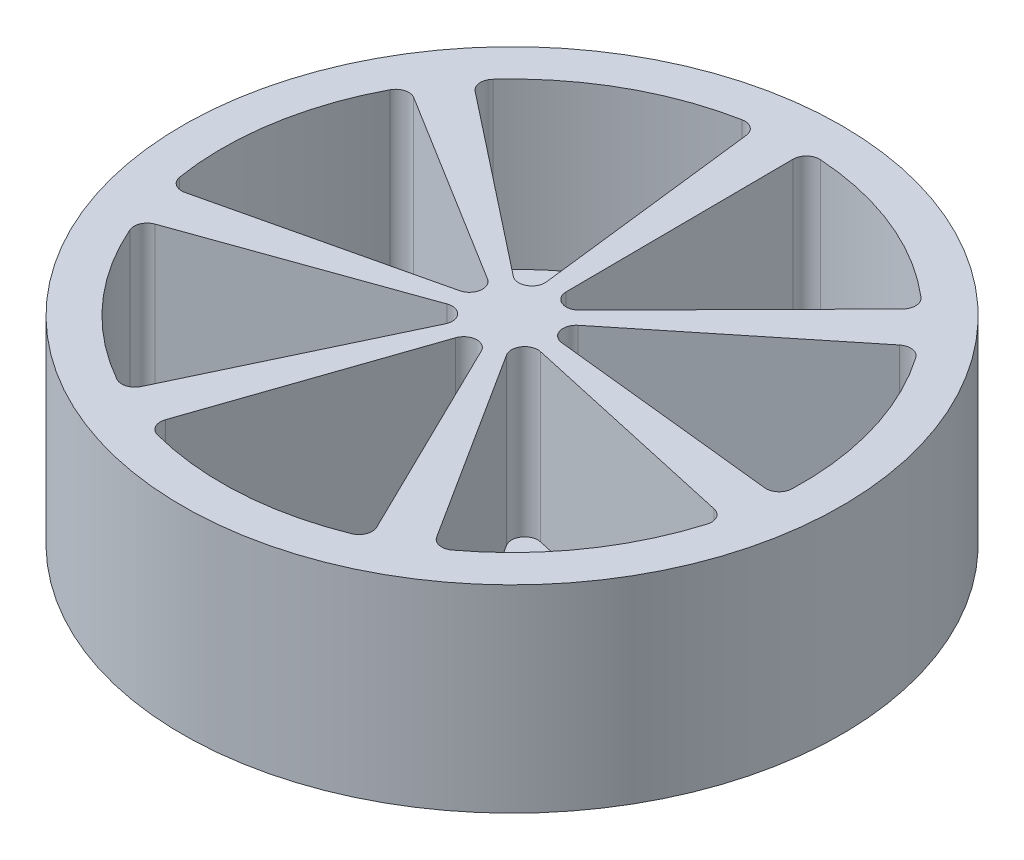
SolidWorks part; units mm, degrees
material "ABS"
ref_plane "Front Plane" through (0, 0, 0) normal (0, 0, 1) x (1, 0, 0)
ref_plane "Top Plane" through (0, 0, 0) normal (0, 1, 0) x (1, 0, 0)
ref_plane "Right Plane" through (0, 0, 0) normal (1, 0, 0) x (0, 0, -1)
sketch "Sketch1" plane through (0, 0, 0) normal (0, 1, 0) x (1, 0, 0)
  circle A0 centre (0, 0) radius 63.5
  dimension "D1" = 127
extrude "Boss-Extrude1" add sketch "Sketch1" along normal blind 38.1
sketch "Sketch2" plane through (0, 38.1, 0) normal (0, 1, 0) x (1, 0, 0)
  line L0 (-1.782, -9.1113) -> (-16.0573, -50.7387)
  line L1 (2.9021, -8.8187) -> (22.2474, -48.3457)
  line L2 (0.2069, -3.3118) -> (23.4176, -50.7365) construction
  line L3 (0, 0) -> (25.1229, -51.3319) construction
  line L4 (0, 0) -> (-18.5387, -54.0596) construction
  line L5 (0.2069, -3.3118) -> (-16.9208, -53.2566) construction
  line L6 (8.7042, -3.2294) -> (51.6692, -12.7493)
  line L9 (6.0125, -7.074) -> (29.6575, -44.1892)
  line L10 (7.9518, 4.7917) -> (42.183, 32.4476)
  line L11 (9.2794, 0.2902) -> (53.0397, -4.3643)
  line L12 (1.2116, 9.2045) -> (0.9321, 53.2107)
  line L13 (5.5587, 7.4359) -> (36.4818, 38.747)
  line L14 (-6.441, 6.6862) -> (-41.0207, 33.9051)
  line L15 (-2.3478, 8.9822) -> (-7.5476, 52.681)
  line L16 (-9.2434, -0.867) -> (-52.0841, -10.9317)
  line L17 (-8.4864, 3.7647) -> (-45.8935, 26.9451)
  line L18 (-5.0853, -7.7673) -> (-23.9271, -47.5368)
  line L19 (-8.2345, -4.2876) -> (-49.6807, -19.081)
  arc A0 (-18.5387, -54.0596) -> (25.1229, -51.3319) centre (0, 0) ccw construction
  circle A1 centre (0, 0) radius 63.5 construction
  arc A2 (-14.3049, -54.018) -> (20.9168, -51.8176) centre (0, 0) ccw
  arc A3 (-16.9208, -53.2566) -> (23.4176, -50.7365) centre (0, 0) ccw construction
  arc A4 (20.9168, -51.8176) -> (22.2474, -48.3457) centre (19.966, -49.4622) ccw
  arc A5 (-16.0573, -50.7387) -> (-14.3049, -54.018) centre (-13.6547, -51.5626) ccw
  arc A6 (-1.782, -9.1113) -> (2.9021, -8.8187) centre (0.6207, -9.9353) cw
  arc A7 (6.0125, -7.074) -> (8.7042, -3.2294) centre (8.1547, -5.7093) cw
  arc A8 (33.314, -44.8637) -> (53.554, -15.9543) centre (0, 0) ccw
  arc A9 (29.6575, -44.1892) -> (33.314, -44.8637) centre (31.7998, -42.8244) ccw
  arc A10 (53.554, -15.9543) -> (51.6692, -12.7493) centre (51.1198, -15.2291) ccw
  arc A11 (9.2794, 0.2902) -> (7.9518, 4.7917) centre (9.548, 2.8159) cw
  arc A12 (55.8468, -1.9261) -> (45.864, 31.9229) centre (0, 0) ccw
  arc A13 (53.0397, -4.3643) -> (55.8468, -1.9261) centre (53.3083, -1.8385) ccw
  arc A14 (45.864, 31.9229) -> (42.183, 32.4476) centre (43.7793, 30.4718) ccw
  arc A15 (5.5587, 7.4359) -> (1.2116, 9.2045) centre (3.7515, 9.2207) cw
  arc A16 (36.3258, 42.4619) -> (3.6374, 55.7615) centre (0, 0) ccw
  arc A17 (36.4818, 38.747) -> (36.3258, 42.4619) centre (34.6746, 40.5318) ccw
  arc A18 (3.6374, 55.7615) -> (0.9321, 53.2107) centre (3.4721, 53.2269) ccw
  arc A19 (-2.3478, 8.9822) -> (-6.441, 6.6862) centre (-4.87, 8.6821) cw
  arc A20 (-10.5493, 54.8752) -> (-41.3282, 37.6106) centre (0, 0) ccw
  arc A21 (-7.5476, 52.681) -> (-10.5493, 54.8752) centre (-10.0698, 52.3809) ccw
  arc A22 (-41.3282, 37.6106) -> (-41.0207, 33.9051) centre (-39.4496, 35.901) ccw
  arc A23 (-8.4864, 3.7647) -> (-9.2434, -0.867) centre (-9.8243, 1.6057) cw
  arc A24 (-49.4805, 25.9664) -> (-55.1728, -8.8619) centre (0, 0) ccw
  arc A25 (-45.8935, 26.9451) -> (-49.4805, 25.9664) centre (-47.2314, 24.7861) ccw
  arc A26 (-55.1728, -8.8619) -> (-52.0841, -10.9317) centre (-52.665, -8.4591) ccw
  arc A27 (-8.2345, -4.2876) -> (-5.0853, -7.7673) centre (-7.3807, -6.6798) cw
  arc A28 (-51.1519, -22.4957) -> (-27.4712, -48.6611) centre (0, 0) ccw
  arc A29 (-49.6807, -19.081) -> (-51.1519, -22.4957) centre (-48.8268, -21.4731) ccw
  arc A30 (-27.4712, -48.6611) -> (-23.9271, -47.5368) centre (-26.2225, -46.4493) ccw
  point P14 (0, 0)
  point P79 (0, 0)
  dimension "D1" = 6.35
  dimension "D3" = 2.54
  dimension "D2" = 1.27
  dimension "D4" = 7
extrude "Cut-Extrude2" cut sketch "Sketch2" against normal offset from surface (31.75 mm away) 6.35 up to face at (0, 0, 63.5)
sketch "Sketch4" plane through (0, 0, 0) normal (0, -1, 0) x (1, 0, 0)
  circle A0 centre (0, 0) radius 6.35
  dimension "D1" = 12.7
extrude "Boss-Extrude2" add sketch "Sketch4" along normal blind 6.35
sketch "Sketch3" plane through (0, 0, 0) normal (0, -1, 0) x (1, 0, 0)
  circle A0 centre (0, 0) radius 2.54
  circle A1 centre (0, 0) radius 2.54 construction
  circle A2 centre (0, 0) radius 2.94
  dimension "D1" = 0.4
extrude "Cut-Extrude3" cut sketch "Sketch3" against normal blind 15.24 and the other way through all
ref_plane "Plane1" through (0, 0, 6.35) normal (0, 0, 1) x (1, 0, 0)
sketch "Sketch5" plane through (0, 0, 6.35) normal (0, 0, 1) x (1, 0, 0)
  line L0 (0, 0) -> (0, -6.35) construction
  line L1 (-6.35, -6.35) -> (6.35, -6.35) construction
  line L2 (-6.35, -3.175) -> (6.35, -3.175) construction
  line L3 (-6.35, 0) -> (-6.35, -6.35) construction
  line L4 (6.35, -6.35) -> (6.35, 0) construction
  circle A0 centre (0, -3.175) radius 1.2639
extrude "Cut-Extrude4" cut sketch "Sketch5" against normal up to next contours A0
